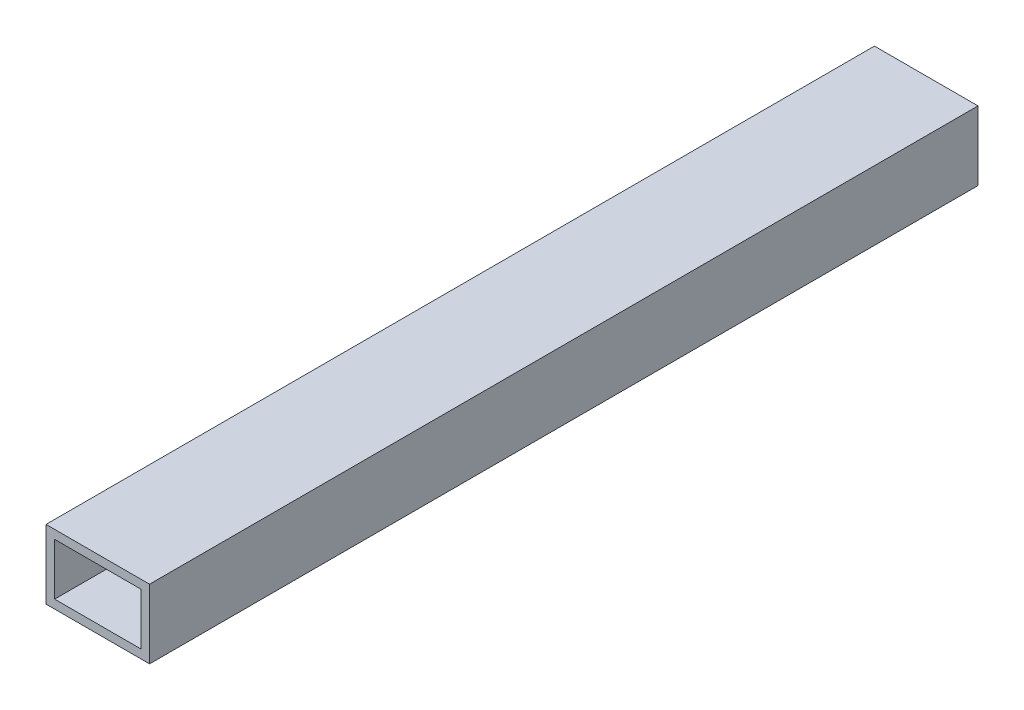
SolidWorks part; units mm, degrees
ref_plane "Front Plane" through (0, 0, 0) normal (0, 0, 1) x (1, 0, 0)
ref_plane "Top Plane" through (0, 0, 0) normal (0, 1, 0) x (1, 0, 0)
ref_plane "Right Plane" through (0, 0, 0) normal (1, 0, 0) x (0, 0, -1)
sketch "Sketch1" plane through (0, 0, 0) normal (0, 0, 1) x (1, 0, 0)
  line L1 (-19.05, 12.7) -> (19.05, 12.7)
  line L2 (-19.05, 12.7) -> (-19.05, -12.7)
  line L3 (-19.05, -12.7) -> (19.05, -12.7)
  line L4 (19.05, 12.7) -> (19.05, -12.7)
  line L5 (-19.05, 12.7) -> (19.05, -12.7) construction
  line L6 (-19.05, -12.7) -> (19.05, 12.7) construction
  point P0 (0, 0)
  dimension "D1" = 38.1
  dimension "D2" = 25.4
extrude "Boss-Extrude1" add sketch "Sketch1" along normal blind 304.8
shell "Shell1" thickness 3.175
